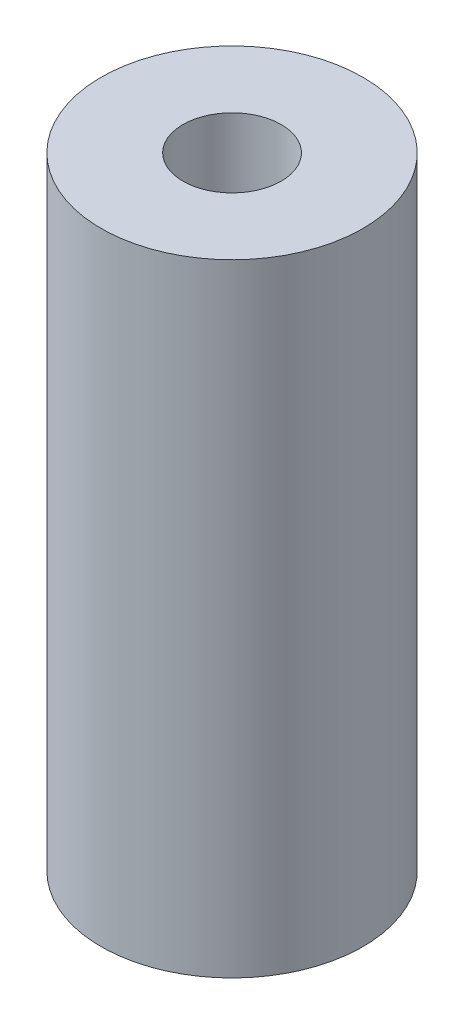
SolidWorks part; units mm, degrees
material "6061-T6 (SS)"
ref_plane "Front" through (0, 0, 0) normal (0, 0, 1) x (1, 0, 0)
ref_plane "Top" through (0, 0, 0) normal (0, 1, 0) x (1, 0, 0)
ref_plane "Right" through (0, 0, 0) normal (1, 0, 0) x (0, 0, -1)
sketch "Sketch1" plane through (0, 0, 0) normal (0, 1, 0) x (1, 0, 0)
  circle A0 centre (0, 0) radius 25.4
  circle A1 centre (0, 0) radius 9.525
  dimension "D1" = 50.8
  dimension "D2" = 19.05
extrude "Boss-Extrude1" add sketch "Sketch1" along normal blind 120.65
sketch "Sketch2" plane through (0, 0, 0) normal (-1, 0, 0) x (0, 0, 1)
  line L0 (-25.4, 88.9) -> (-25.4, 38.1)
  line L1 (-25.4, 88.9) -> (25.4, 88.9)
  line L2 (-25.4, 38.1) -> (25.4, 38.1)
  line L3 (25.4, 88.9) -> (25.4, 38.1)
  line L5 (0, 88.9) -> (0, 0) construction
  point P3 (0, 88.9)
  dimension "D1" = 50.8
  dimension "D2" = 38.1
  dimension "D3" = 50.8
split line "Split Line1" [suppressed]
